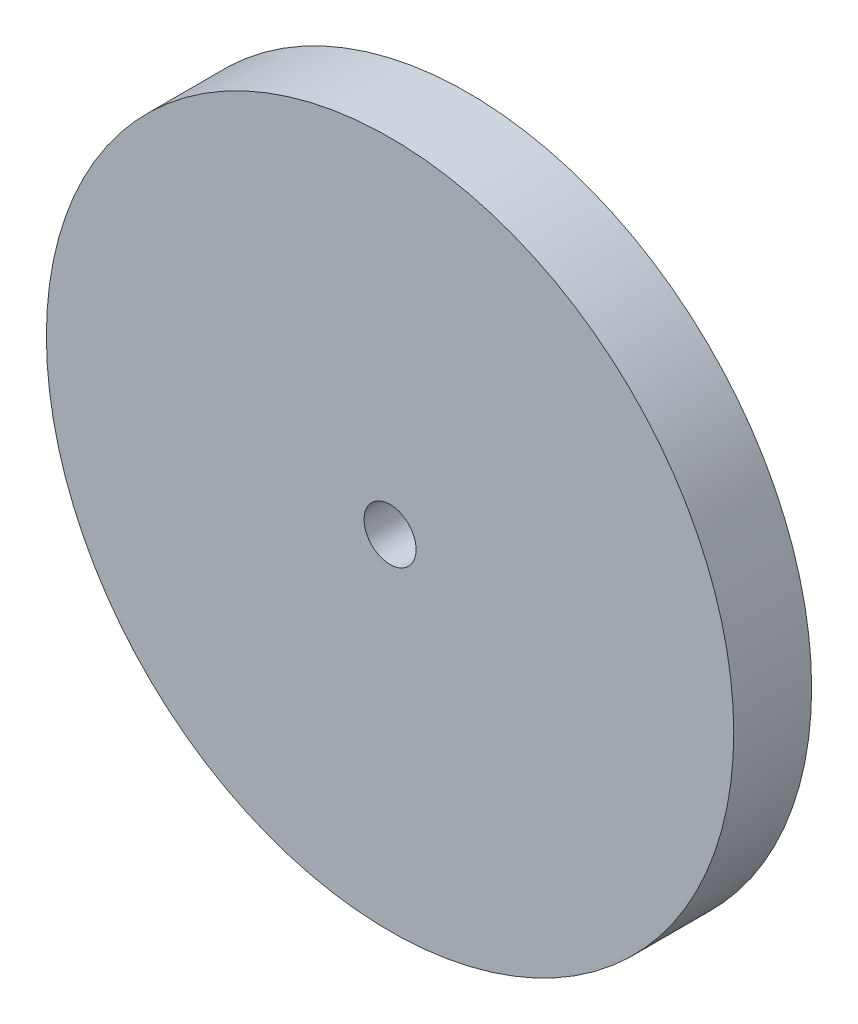
SolidWorks part; units mm, degrees
ref_plane "Front Plane" through (0, 0, 0) normal (0, 0, 1) x (1, 0, 0)
ref_plane "Top Plane" through (0, 0, 0) normal (0, 1, 0) x (1, 0, 0)
ref_plane "Right Plane" through (0, 0, 0) normal (1, 0, 0) x (0, 0, -1)
sketch "Sketch1" plane through (0, 0, 0) normal (0, 0, 1) x (1, 0, 0)
  circle A0 centre (0, 0) radius 24.6683
  circle A1 centre (0, 0) radius 1.8669
  dimension "D1" = 49.3365
  dimension "D2" = 3.7338
extrude "Boss-Extrude1" add sketch "Sketch1" along normal blind 5.588
